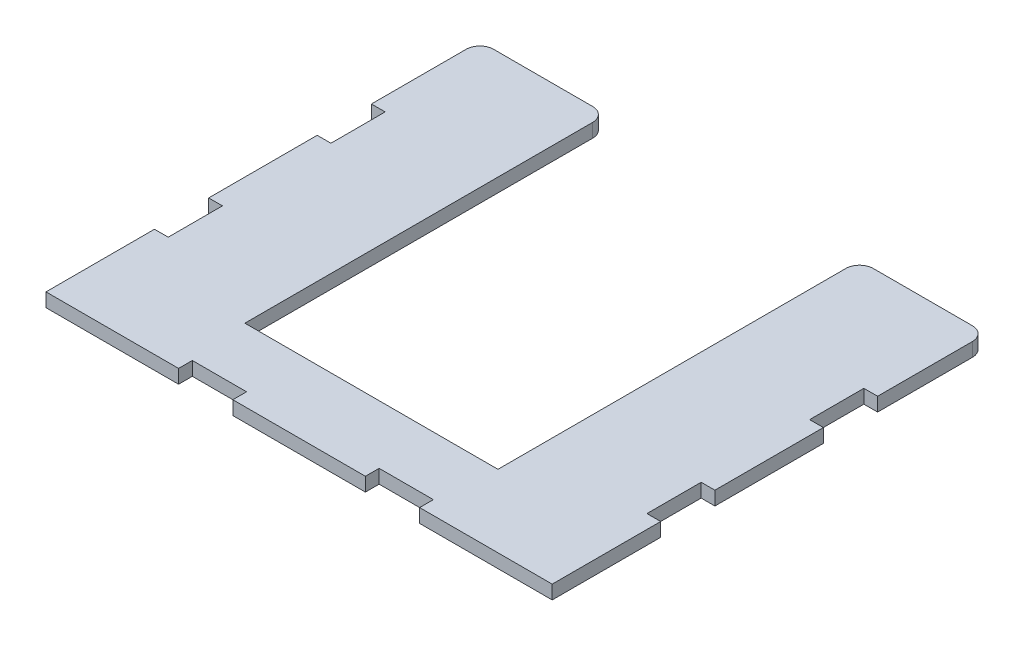
SolidWorks part; units mm, degrees
ref_plane "Front Plane" through (0, 0, 0) normal (0, 0, 1) x (1, 0, 0)
ref_plane "Top Plane" through (0, 0, 0) normal (0, 1, 0) x (1, 0, 0)
ref_plane "Right Plane" through (0, 0, 0) normal (1, 0, 0) x (0, 0, -1)
sketch "Sketch1" plane through (0, 0, 0) normal (0, 1, 0) x (1, 0, 0)
  line L1 (0, 0) -> (177.8, 0)
  line L2 (0, 0) -> (0, 152.4)
  line L3 (0, 152.4) -> (177.8, 152.4)
  line L4 (177.8, 0) -> (177.8, 152.4)
  dimension "D1" = 177.8
  dimension "D2" = 152.4
extrude "Boss-Extrude1" add sketch "Sketch1" along normal blind 4.826
sketch "Sketch2" plane through (0, 4.826, 0) normal (0, 1, 0) x (1, 0, 0)
  line L0 (177.8, 152.4) -> (0, 152.4) construction
  line L1 (44.45, 152.4) -> (133.35, 152.4)
  line L2 (44.45, 152.4) -> (44.45, 25.4)
  line L3 (44.45, 25.4) -> (133.35, 25.4)
  line L4 (133.35, 152.4) -> (133.35, 25.4)
  line L5 (44.45, 25.4) -> (0, 25.4) construction
  line L6 (0, 152.4) -> (0, 0) construction
  line L7 (133.35, 25.4) -> (177.8, 25.4) construction
  line L8 (177.8, 0) -> (177.8, 152.4) construction
  dimension "D1" = 127
  dimension "D2" = 88.9
extrude "Center Cutout" cut sketch "Sketch2" against normal through all
sketch "Sketch3" plane through (0, 4.826, 0) normal (0, 1, 0) x (1, 0, 0)
  line L1 (0, 0) -> (177.8, 0) construction
  line L2 (46.5667, 0) -> (65.6167, 0)
  line L3 (46.5667, 0) -> (46.5667, 4.826)
  line L4 (46.5667, 4.826) -> (65.6167, 4.826)
  line L5 (65.6167, 0) -> (65.6167, 4.826)
  line L6 (46.5667, 4.826) -> (0, 4.826) construction
  line L7 (112.1833, 0) -> (131.2333, 0)
  line L8 (112.1833, 0) -> (112.1833, 4.826)
  line L9 (112.1833, 4.826) -> (131.2333, 4.826)
  line L10 (131.2333, 0) -> (131.2333, 4.826)
  line L11 (0, 152.4) -> (0, 0) construction
  line L12 (65.6167, 4.826) -> (112.1833, 4.826) construction
  line L13 (131.2333, 4.826) -> (177.8, 4.826) construction
  line L14 (177.8, 0) -> (177.8, 152.4) construction
  dimension "D1" = 4.826
  dimension "D2" = 19.05
extrude "Back Edge Slots" cut sketch "Sketch3" against normal through all
sketch "Sketch5" plane through (0, 4.826, 0) normal (0, 1, 0) x (1, 0, 0)
  line L2 (0, 152.4) -> (0, 0) construction
  line L3 (0, 114.3) -> (4.826, 114.3)
  line L4 (0, 114.3) -> (0, 95.25)
  line L5 (0, 95.25) -> (4.826, 95.25)
  line L6 (4.826, 114.3) -> (4.826, 95.25)
  line L7 (177.8, 0) -> (177.8, 152.4) construction
  line L8 (0, 57.15) -> (4.826, 57.15)
  line L9 (0, 57.15) -> (0, 38.1)
  line L10 (0, 38.1) -> (4.826, 38.1)
  line L12 (4.826, 57.15) -> (4.826, 38.1)
  line L13 (177.8, 114.3) -> (172.974, 114.3)
  line L14 (177.8, 114.3) -> (177.8, 95.25)
  line L18 (177.8, 95.25) -> (172.974, 95.25)
  line L19 (172.974, 114.3) -> (172.974, 95.25)
  line L20 (4.826, 114.3) -> (4.826, 152.4) construction
  line L21 (177.8, 57.15) -> (172.974, 57.15)
  line L22 (177.8, 57.15) -> (177.8, 38.1)
  line L23 (177.8, 38.1) -> (172.974, 38.1)
  line L24 (172.974, 57.15) -> (172.974, 38.1)
  line L25 (44.45, 152.4) -> (0, 152.4) construction
  line L26 (4.826, 95.25) -> (4.826, 57.15) construction
  line L27 (4.826, 38.1) -> (4.826, 0) construction
  line L28 (0, 0) -> (46.5667, 0) construction
  line L29 (172.974, 38.1) -> (172.974, 0) construction
  line L30 (131.2333, 0) -> (177.8, 0) construction
  line L31 (172.974, 57.15) -> (172.974, 95.25) construction
  line L32 (172.974, 114.3) -> (172.974, 152.4) construction
  line L33 (177.8, 152.4) -> (133.35, 152.4) construction
  dimension "D1" = 19.05
  dimension "D2" = 4.826
extrude "Side Edge Slots" cut sketch "Sketch5" against normal through all
fillet "Leading Edge Fillet" radius 4.826 4 edges at (0, 2.413, -152.4) (177.8, 2.413, -152.4) (44.45, 2.413, -152.4) (133.35, 2.413, -152.4)
equation "\"material\"= \"gmaterial@Forklift_Assembly.assembly\""
equation "\"D1@Boss-Extrude1\"=\"material\""
equation "\"D1@Sketch3\"=\"material\""
equation "\"D2@Sketch5\"=\"material\""
equation "\"D1@Leading Edge Fillet\"=\"material\""
